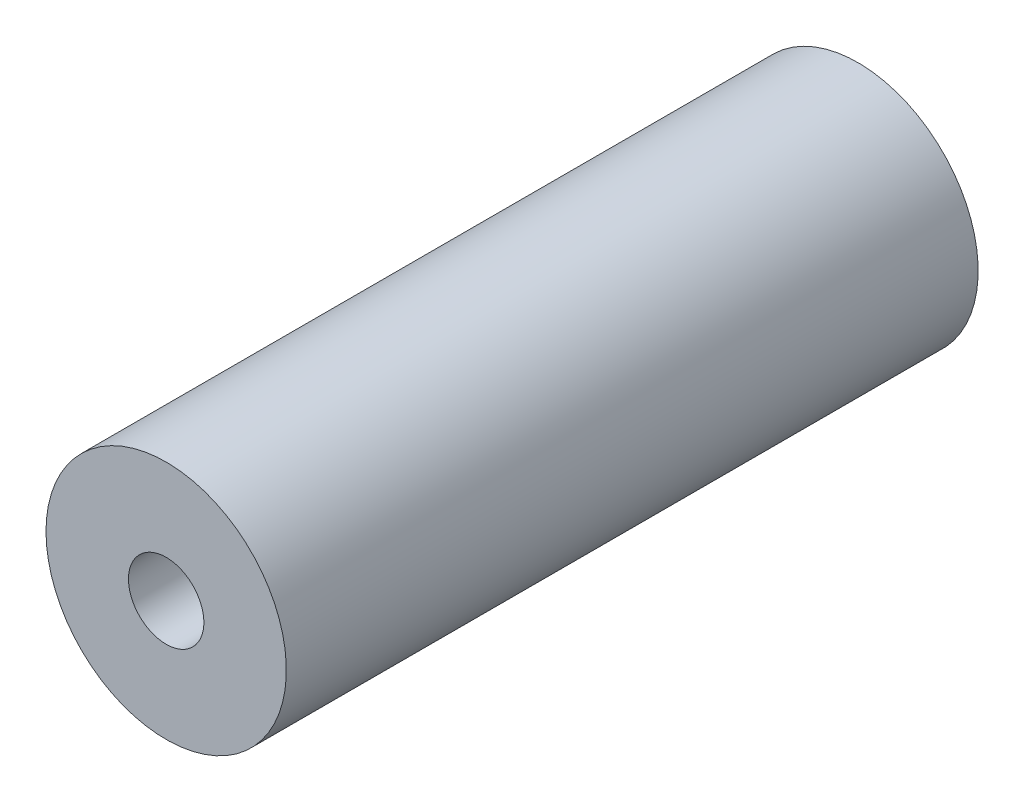
SolidWorks part; units mm, degrees
material "6061-T6 (SS)"
ref_plane "Front Plane" through (0, 0, 0) normal (0, 0, 1) x (1, 0, 0)
ref_plane "Top Plane" through (0, 0, 0) normal (0, 1, 0) x (1, 0, 0)
ref_plane "Right Plane" through (0, 0, 0) normal (1, 0, 0) x (0, 0, -1)
sketch "Sketch1" plane through (0, 0, 0) normal (1, 0, 0) x (0, 0, -1)
  line L0 (24.0405, 0) -> (-23.7032, 0) construction
  line L2 (-22.8473, 7.9375) -> (22.8473, 7.9375)
  line L3 (-22.8473, 7.9375) -> (-22.8473, 2.4892)
  line L4 (-22.8473, 2.4892) -> (22.8473, 2.4892)
  line L5 (22.8473, 7.9375) -> (22.8473, 2.4892)
  point P7 (0, 2.4892)
  dimension "D1" = 4.9784
  dimension "D2" = 15.875
  dimension "D3" = 45.6946
revolve "Revolve1" add sketch "Sketch1" angle 360 about L0
